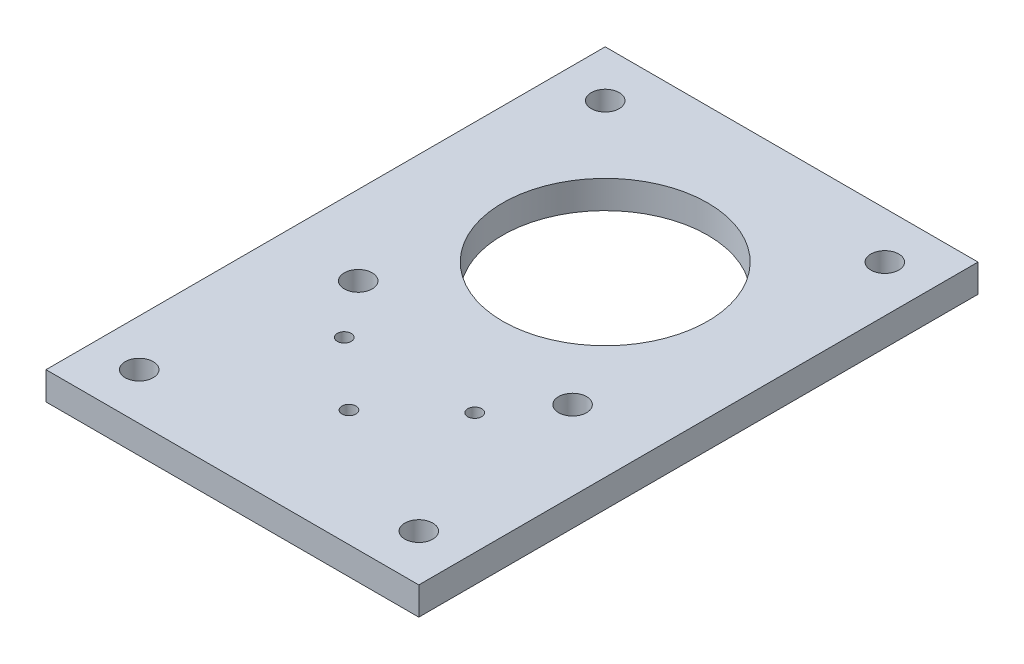
SolidWorks part; units mm, degrees
ref_plane "前视基准面" through (0, 0, 0) normal (0, 0, 1) x (1, 0, 0)
ref_plane "上视基准面" through (0, 0, 0) normal (0, 1, 0) x (1, 0, 0)
ref_plane "右视基准面" through (0, 0, 0) normal (1, 0, 0) x (0, 0, -1)
sketch "草图1" plane through (0, 0, 0) normal (0, 1, 0) x (1, 0, 0)
  line L1 (-20, 20) -> (20, 20)
  line L2 (-20, 20) -> (-20, -40)
  line L3 (-20, -40) -> (20, -40)
  line L4 (20, 20) -> (20, -40)
  circle A0 centre (0, 0) radius 11
  circle A1 centre (-15, 15) radius 1.5
  circle A2 centre (15, 15) radius 1.5
  circle A3 centre (15, -35) radius 1.5
  circle A4 centre (-15, -35) radius 1.5
  circle A5 centre (0, -27.5) radius 0.75
  circle A6 centre (-7, -21) radius 0.75
  circle A7 centre (7, -21) radius 0.75
  circle A8 centre (-11.5, -15) radius 1.5
  circle A9 centre (11.5, -15) radius 1.5
  dimension "D3" = 20
  dimension "D5" = 22
  dimension "D6" = 3
  dimension "D7" = 3
  dimension "D8" = 3
  dimension "D9" = 3
  dimension "D13" = 5
  dimension "D14" = 5
  dimension "D15" = 5
  dimension "D19" = 11.5
  dimension "D20" = 3
  dimension "D21" = 3
  dimension "D24" = 1.5
  dimension "D25" = 1.5
  dimension "D26" = 1.5
  dimension "D29" = 7
  dimension "D30" = 14
  dimension "D1" = 40
  dimension "D2" = 60
  dimension "D4" = 20
  dimension "D10" = 5
  dimension "D11" = 5
  dimension "D12" = 5
  dimension "D16" = 5
  dimension "D17" = 5
  dimension "D18" = 15
  dimension "D22" = 15
  dimension "D23" = 11.5
  dimension "D27" = 27.5
  dimension "D28" = 21
extrude "凸台-拉伸1" add sketch "草图1" along normal blind 3
